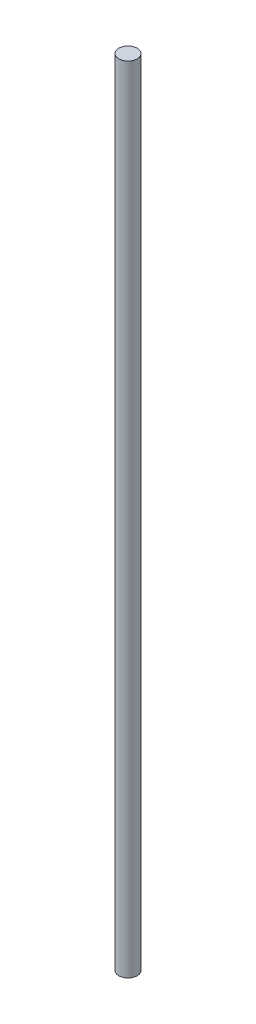
SolidWorks part; units mm, degrees
material "201 Annealed Stainless Steel (SS)"
ref_plane "Front Plane" through (0, 0, 0) normal (0, 0, 1) x (1, 0, 0)
ref_plane "Top Plane" through (0, 0, 0) normal (0, 1, 0) x (1, 0, 0)
ref_plane "Right Plane" through (0, 0, 0) normal (1, 0, 0) x (0, 0, -1)
sketch "Sketch1" plane through (0, 0, 0) normal (0, 1, 0) x (1, 0, 0)
  circle A0 centre (-10.6771, -0.935) radius 4
  dimension "D1" = 8
extrude "Boss-Extrude1" add sketch "Sketch1" along normal blind 345
